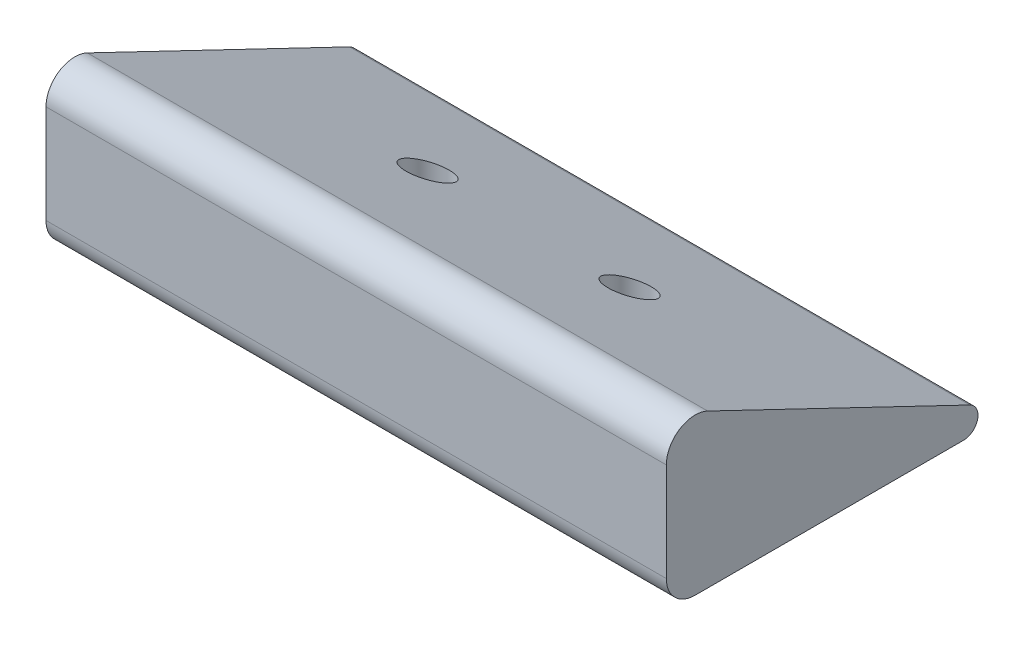
SolidWorks part; units mm, degrees
material "Rubber"
ref_plane "Front Plane" through (0, 0, 0) normal (0, 0, 1) x (1, 0, 0)
ref_plane "Top Plane" through (0, 0, 0) normal (0, 1, 0) x (1, 0, 0)
ref_plane "Right Plane" through (0, 0, 0) normal (1, 0, 0) x (0, 0, -1)
sketch "Sketch1" plane through (0, 0, 0) normal (1, 0, 0) x (0, 0, -1)
  line L0 (2, 0) -> (20.6058, 0)
  line L1 (21.0385, 1.9015) -> (2.8655, 10.6246)
  line L2 (0, 8.8215) -> (0, 2)
  arc A0 (2.8655, 10.6246) -> (0, 8.8215) centre (2, 8.8215) ccw
  arc A1 (2, 0) -> (0, 2) centre (2, 2) cw
  arc A2 (21.0385, 1.9015) -> (20.6058, 0) centre (20.6058, 1) cw
  point P6 (0, 12)
  point P9 (0, 0)
  point P12 (25, 0)
  dimension "D3" = 2
  dimension "D4" = 1
  dimension "D1" = 25
  dimension "D2" = 12
extrude "Boss-Extrude1" add sketch "Sketch1" along normal blind 43
ref_plane "Plane1" through (0, 10, 0) normal (0, 1, 0) x (1, 0, 0)
sketch "Sketch2" plane through (0, 10, 0) normal (0, 1, 0) x (1, 0, 0)
  line L0 (43, 11.952) -> (0, 11.952) construction
  line L1 (43, 21.0385) -> (43, 2.8655) construction
  line L2 (0, 21.0385) -> (0, 2.8655) construction
  line L3 (21.5, 11.952) -> (21.5, 16.6997) construction
  circle A0 centre (14.5, 11.952) radius 1.5
  circle A1 centre (28.5, 11.952) radius 1.5
  dimension "D1" = 3
  dimension "D2" = 14
extrude "Cut-Extrude1" cut sketch "Sketch2" against normal through all
